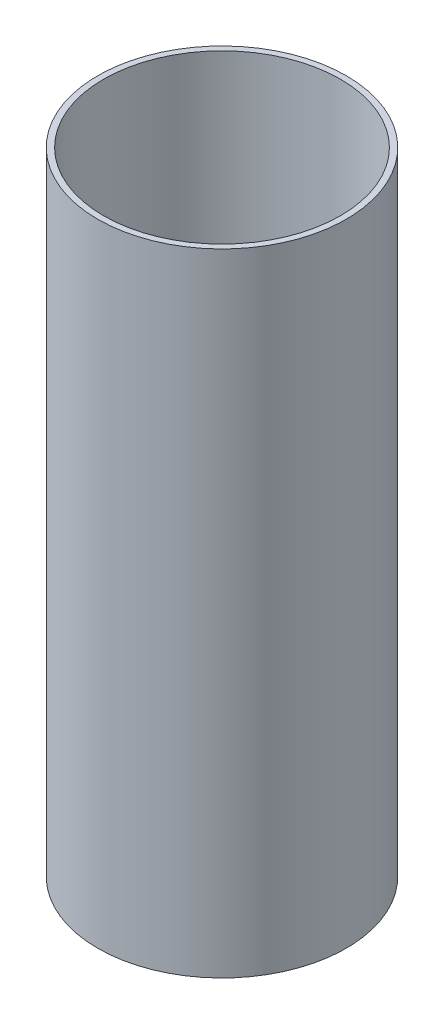
SolidWorks part; units mm, degrees
ref_plane "Front Plane" through (0, 0, 0) normal (0, 0, 1) x (1, 0, 0)
ref_plane "Top Plane" through (0, 0, 0) normal (0, 1, 0) x (1, 0, 0)
ref_plane "Right Plane" through (0, 0, 0) normal (1, 0, 0) x (0, 0, -1)
sketch "Sketch1" plane through (0, 0, 0) normal (0, 1, 0) x (1, 0, 0)
  circle A0 centre (0, 0) radius 38.1
  circle A1 centre (0, 0) radius 40.005
  dimension "D1" = 76.2
  dimension "D2" = 80.01
extrude "Boss-Extrude1" add sketch "Sketch1" along normal blind 203.2
